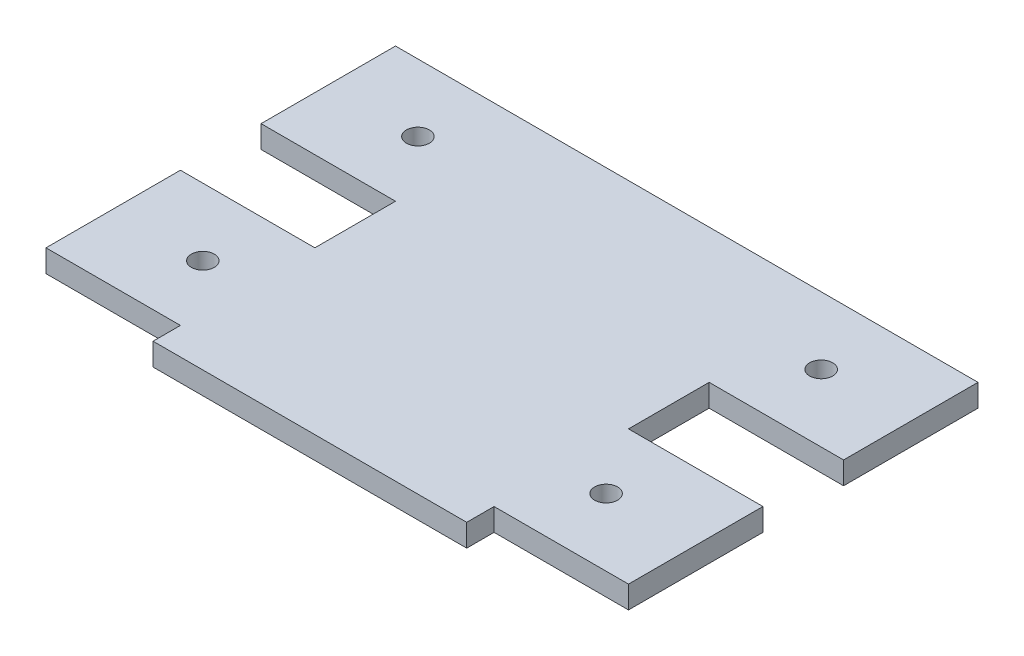
SolidWorks part; units mm, degrees
ref_plane "Front Plane" through (0, 0, 0) normal (0, 0, 1) x (1, 0, 0)
ref_plane "Top Plane" through (0, 0, 0) normal (0, 1, 0) x (1, 0, 0)
ref_plane "Right Plane" through (0, 0, 0) normal (1, 0, 0) x (0, 0, -1)
sketch "Sketch2" plane through (0, 0, 0) normal (0, 1, 0) x (1, 0, 0)
  line L0 (0, 40.894) -> (-19.05, 40.894)
  line L1 (0, 0) -> (44.45, 0)
  line L2 (0, 0) -> (0, 10.414)
  line L3 (-19.05, 40.894) -> (-19.05, 59.944)
  line L4 (44.45, 0) -> (44.45, 10.414)
  line L5 (-19.05, 59.944) -> (0, 59.944)
  line L6 (0, 59.944) -> (0, 70.358)
  line L7 (44.45, 40.894) -> (44.45, 29.464)
  line L8 (44.45, 29.464) -> (63.5, 29.464)
  line L9 (63.5, 29.464) -> (63.5, 10.414)
  line L10 (63.5, 10.414) -> (44.45, 10.414)
  line L11 (0, 70.358) -> (44.45, 70.358)
  line L12 (44.45, 70.358) -> (44.45, 59.944)
  line L13 (44.45, 59.944) -> (63.5, 59.944)
  line L14 (0, 29.464) -> (-19.05, 29.464)
  line L15 (-19.05, 29.464) -> (-19.05, 10.414)
  line L16 (-19.05, 10.414) -> (0, 10.414)
  line L17 (63.5, 59.944) -> (63.5, 40.894)
  line L19 (63.5, 40.894) -> (44.45, 40.894)
  line L20 (0, 29.464) -> (0, 40.894)
  dimension "D1" = 44.45
  dimension "D2" = 10.414
  dimension "D3" = 19.05
  dimension "D4" = 19.05
  dimension "D5" = 11.43
  dimension "D6" = 10.414
extrude "Boss-Extrude1" add sketch "Sketch2" along normal blind 3.175
hole_wizard "#4 Clearance Hole1" positions "Sketch4" profile "Sketch3" hole size "#4" standard "ANSI Inch" end condition through all
sketch "Sketch4" plane through (0, 3.175, 0) normal (0, 1, 0) x (1, 0, 0)
  line L3 (0, 10.414) -> (0, 0) construction
  line L4 (44.45, 0) -> (44.45, 10.414) construction
  line L5 (-19.05, 10.414) -> (0, 10.414) construction
  line L6 (44.45, 10.414) -> (63.5, 10.414) construction
  line L9 (0, 70.358) -> (0, 59.944) construction
  line L11 (0, 59.944) -> (-19.05, 59.944) construction
  line L12 (44.45, 59.944) -> (44.45, 70.358) construction
  line L14 (63.5, 59.944) -> (44.45, 59.944) construction
  point P0 (-6.35, 50.419)
  point P2 (50.8, 50.419)
  point P4 (50.8, 19.939)
  point P6 (-6.35, 19.939)
  point P31 (-9.525, 59.944)
  dimension "D1" = 6.35
  dimension "D2" = 6.35
  dimension "D3" = 6.35
  dimension "D4" = 6.35
  dimension "D5" = 9.525
  dimension "D6" = 9.525
  dimension "D7" = 9.525
  dimension "D8" = 9.525
sketch "Sketch3" plane through (-6.35, 3.175, -50.419) normal (1, 0, 0) x (0, 0, 1)
  line L0 (0, 0) -> (0, 3.175)
  line L1 (0, 3.175) -> (1.6319, 3.175)
  line L2 (1.6319, 3.175) -> (1.6319, 0)
  line L5 (1.6319, 0) -> (0, 0)
  line L11 (0, -6.35) -> (0, 107.95) construction
  dimension "Thru Hole Dia." = 3.2639
  dimension "Thru Hole Depth" = 3.175
sketch "Sketch5" [suppressed] plane through (0, 3.175, 0) normal (0, 1, 0) x (1, 0, 0)
  line L1 (-34.6876, 155.9178) -> (94.3937, 155.9178)
  line L2 (-34.6876, 155.9178) -> (-34.6876, 116.4513)
  line L3 (-34.6876, 116.4513) -> (94.3937, 116.4513)
  line L4 (94.3937, 155.9178) -> (94.3937, 116.4513)
extrude "Cut-Extrude1" [suppressed] cut sketch "Sketch5" against normal through all
sketch "Sketch6" plane through (0, 0, 0) normal (0, -1, 0) x (1, 0, 0)
  line L1 (44.45, -59.944) -> (-2.9125, -59.944)
  line L2 (44.45, -59.944) -> (44.45, -80.0706)
  line L3 (44.45, -80.0706) -> (-2.9125, -80.0706)
  line L4 (-2.9125, -59.944) -> (-2.9125, -80.0706)
extrude "Cut-Extrude2" cut sketch "Sketch6" against normal through all
sketch "Sketch7" [suppressed] plane through (0, 0, 0) normal (0, -1, 0) x (1, 0, 0)
  line L1 (44.45, -77.8185) -> (-7.6674, -77.8185)
  line L2 (44.45, -77.8185) -> (44.45, -104.7576)
  line L3 (44.45, -104.7576) -> (-7.6674, -104.7576)
  line L4 (-7.6674, -77.8185) -> (-7.6674, -104.7576)
extrude "Cut-Extrude3" [suppressed] cut sketch "Sketch7" against normal through all
sketch "Sketch8" plane through (0, 0, 0) normal (0, -1, 0) x (1, 0, 0)
  line L1 (52.6847, 15.2134) -> (-4.5354, 15.2134)
  line L2 (52.6847, 15.2134) -> (52.6847, -6.5368)
  line L3 (52.6847, -6.5368) -> (-4.5354, -6.5368)
  line L4 (-4.5354, 15.2134) -> (-4.5354, -6.5368)
extrude "Cut-Extrude4" cut sketch "Sketch8" against normal through all
